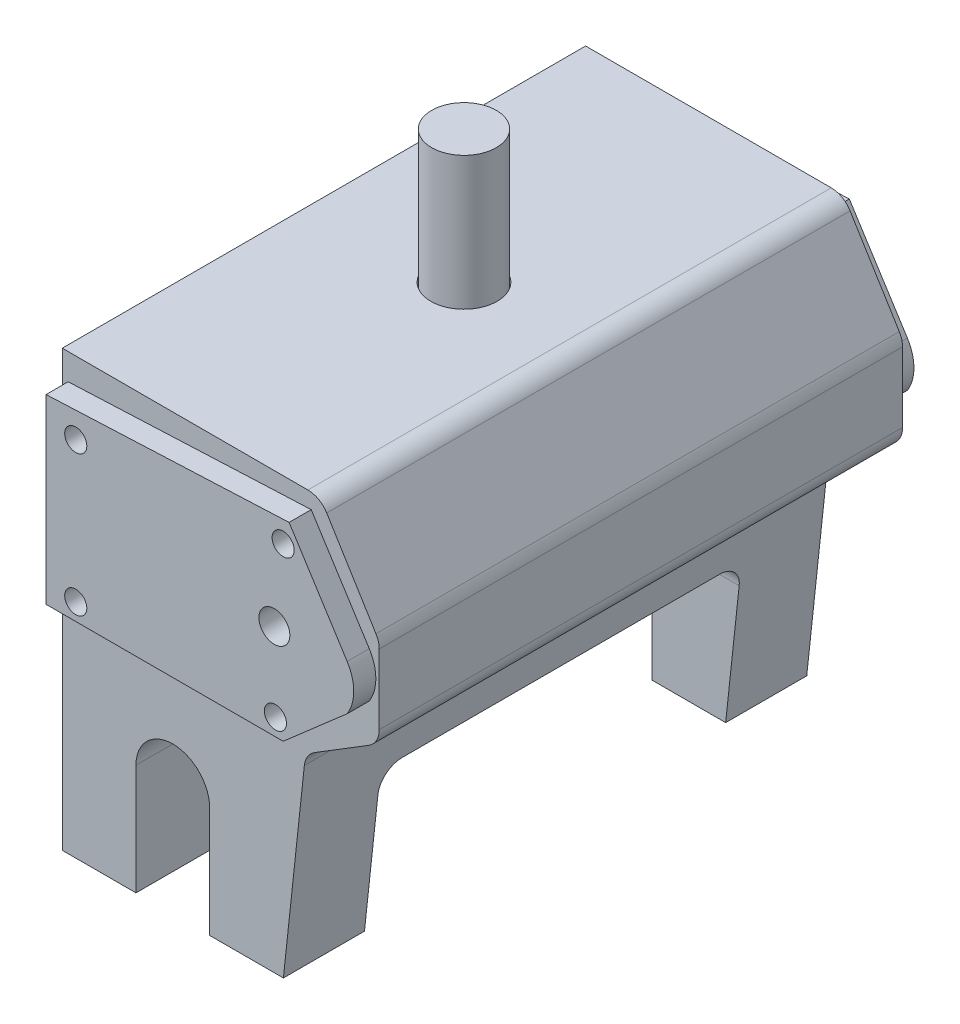
SolidWorks part; units mm, degrees
ref_plane "前视基准面" through (0, 0, 0) normal (0, 0, 1) x (1, 0, 0)
ref_plane "上视基准面" through (0, 0, 0) normal (0, 1, 0) x (1, 0, 0)
ref_plane "右视基准面" through (0, 0, 0) normal (1, 0, 0) x (0, 0, -1)
sketch "草图1" plane through (0, 0, 0) normal (0, 0, 1) x (1, 0, 0)
  line L0 (-32.9666, -19.8934) -> (-32.9666, 39.1066)
  line L1 (-32.9666, 39.1066) -> (0.357, 39.1066)
  line L2 (2.9119, 37.6788) -> (9.5883, 26.8297)
  line L3 (10.0334, 25.2574) -> (10.0334, 15.7829)
  line L4 (8.6057, 13.228) -> (1.2862, 8.7237)
  line L5 (-0.1242, 6.4901) -> (-2.9666, -19.8934)
  line L6 (-2.9666, -19.8934) -> (-12.9666, -19.8934)
  line L7 (-12.9666, -19.8934) -> (-12.9666, -4.8934)
  line L9 (-22.9666, -4.8934) -> (-22.9666, -19.8934)
  line L10 (-22.9666, -19.8934) -> (-32.9666, -19.8934)
  arc A0 (2.9119, 37.6788) -> (0.357, 39.1066) centre (0.357, 36.1066) ccw
  arc A1 (10.0334, 25.2574) -> (9.5883, 26.8297) centre (7.0334, 25.2574) ccw
  arc A2 (8.6057, 13.228) -> (10.0334, 15.7829) centre (7.0334, 15.7829) ccw
  arc A3 (-0.1242, 6.4901) -> (1.2862, 8.7237) centre (2.8585, 6.1687) cw
  arc A4 (-12.9666, -4.8934) -> (-22.9666, -4.8934) centre (-17.9666, -4.8934) ccw
  point P13 (2.0334, 39.1066)
  point P16 (10.0334, 26.1066)
  point P19 (10.0334, 14.1066)
  point P22 (0.0334, 7.9527)
  dimension "D11" = 3
  dimension "D1" = 43
  dimension "D2" = 59
  dimension "D3" = 59
  dimension "D4" = 10
  dimension "D5" = 10
  dimension "D6" = 10
  dimension "D7" = 12
  dimension "D8" = 33
  dimension "D9" = 34
  dimension "D10" = 35
  dimension "D12" = 15
extrude "拉伸1" add sketch "草图1" along normal blind 71
sketch "草图2" plane through (-32.9666, 0, 0) normal (-1, 0, 0) x (0, 0, 1)
  line L0 (11, -19.8934) -> (11, -2.8934)
  line L1 (71, -19.8934) -> (0, -19.8934) construction
  line L2 (14, 0.1066) -> (57, 0.1066)
  line L3 (60, -2.8934) -> (60, -19.8934)
  line L4 (11, -19.8934) -> (60, -19.8934)
  line L5 (0, 39.1066) -> (0, -19.8934) construction
  arc A0 (14, 0.1066) -> (11, -2.8934) centre (14, -2.8934) ccw
  arc A1 (60, -2.8934) -> (57, 0.1066) centre (57, -2.8934) ccw
  dimension "D1" = 3
  dimension "D2" = 49
  dimension "D3" = 20
  dimension "D4" = 11
extrude "拉伸2" cut sketch "草图2" against normal blind 71
sketch "草图3" plane through (0, 0, 71) normal (0, 0, 1) x (1, 0, 0)
  line L0 (-28.5023, 32.8704) -> (-28.5023, 14.3082)
  line L2 (0, 14.3082) -> (0, 32.8704)
  line L4 (0, 32.8704) -> (-28.5023, 32.8704)
  line L5 (-28.5023, 14.3082) -> (0, 14.3082)
extrude "拉伸3" cut sketch "草图3" against normal blind 71
sketch "草图4" plane through (0, 0, 71) normal (0, 0, 1) x (1, 0, 0)
  line L0 (-32.1659, 13.6976) -> (-32.1659, 35.557)
  line L1 (-32.1659, 35.557) -> (0.8064, 37.0224)
  line L2 (0.8064, 37.0224) -> (8.6831, 24.6273)
  line L3 (8.6831, 18.4743) -> (0, 10.9073)
  line L4 (0, 10.9073) -> (-32.1659, 10.9073)
  line L5 (-32.1659, 10.9073) -> (-32.1659, 13.6976)
  arc A0 (8.6831, 24.6273) -> (8.6831, 18.4743) centre (3.8418, 21.5508) cw
extrude "拉伸4" add sketch "草图4" along normal blind 3
sketch "草图5" plane through (0, 0, 74) normal (0, 0, 1) x (1, 0, 0)
  circle A0 centre (-28.136, 32.2598) radius 1.5
  circle A1 centre (0, 34.0916) radius 1.5
  circle A2 centre (-1.0492, 13.2091) radius 1.5
  circle A3 centre (-28.136, 13.2091) radius 1.5
  dimension "D1" = 3
  dimension "D2" = 3
  dimension "D3" = 3
  dimension "D4" = 3
extrude "拉伸5" cut sketch "草图5" against normal blind 10
ref_plane "基准面1" through (0, 0, 36) normal (0, 0, -1) x (-1, 0, 0)
mirror "镜向2" about plane through (0, 0, 36) normal (0, 0, -1) of "拉伸5", "拉伸4"
sketch "草图6" plane through (0, 39.1066, 0) normal (0, 1, 0) x (1, 0, 0)
  line L0 (23.65, -36) -> (-23.65, -36) construction
  line L1 (-32.9666, -71) -> (-32.9666, 0) construction
  circle A0 centre (-13.4666, -36) radius 4.5
  dimension "D2" = 9
  dimension "D1" = 19.5
extrude "拉伸6" cut sketch "草图6" against normal blind 10
sketch "草图7" plane through (0, 0, 36) normal (0, 0, -1) x (-1, 0, 0)
  line L0 (13.4666, 60.8563) -> (13.4666, 12.2571) construction
  line L3 (17.8519, 32.8704) -> (25.4738, 32.8704)
  line L4 (0.871, 32.8704) -> (26.7659, 32.8704) construction
  line L5 (25.4738, 32.8704) -> (25.4738, 16.7521)
  line L6 (25.4738, 16.7521) -> (13.4666, 16.7521)
  line L7 (13.4666, 16.7521) -> (13.4666, 57.1066)
  line L9 (17.8519, 32.8704) -> (17.8519, 57.1066)
  line L10 (-0.357, 39.1066) -> (32.9666, 39.1066) construction
  line L11 (17.8519, 57.1066) -> (13.4666, 57.1066)
  dimension "D1" = 18
revolve "旋转1" add sketch "草图7" angle 360 about L0
sketch "草图8" plane through (0, -19.8934, 0) normal (0, -1, 0) x (1, 0, 0)
  line L0 (-23.65, 36) -> (23.65, 36) construction
  line L1 (-32.9666, 71) -> (-32.9666, 60) construction
  line L2 (-32.9666, 11) -> (-32.9666, 0) construction
  circle A0 centre (-27.9666, 65.5) radius 2.1
  circle A1 centre (-7.9666, 66) radius 2.1
  circle A2 centre (-27.9666, 6) radius 2.1
  circle A3 centre (-7.9666, 6) radius 2.1
  dimension "D1" = 4.2
  dimension "D2" = 4.2
  dimension "D3" = 4.2
  dimension "D4" = 4.2
  dimension "D6" = 60
  dimension "D7" = 30
  dimension "D8" = 20
  dimension "D5" = 20
  dimension "D9" = 5
  dimension "D10" = 5
extrude "拉伸7" cut sketch "草图8" against normal blind 15
sketch "草图9" plane through (0, 0, -2) normal (0, 0, -1) x (-1, 0, 0)
  circle A0 centre (1.1892, 23.7916) radius 2.1
  dimension "D1" = 4.2
extrude "拉伸8" cut sketch "草图9" against normal through all
